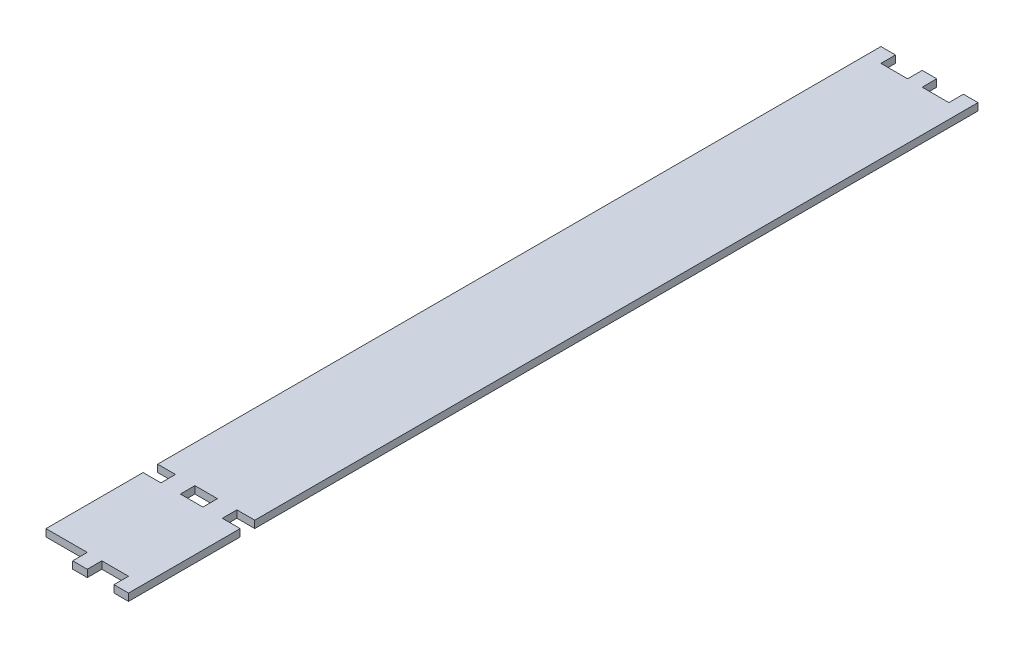
SolidWorks part; units mm, degrees
ref_plane "Plan de face" through (0, 0, 0) normal (0, 0, 1) x (1, 0, 0)
ref_plane "Plan de dessus" through (0, 0, 0) normal (0, 1, 0) x (1, 0, 0)
ref_plane "Plan de droite" through (0, 0, 0) normal (1, 0, 0) x (0, 0, -1)
sketch "Esquisse1" plane through (0, 0, 0) normal (0, 0, 1) x (1, 0, 0)
  line L1 (0, 0) -> (40, 0)
  line L2 (0, 0) -> (0, 3)
  line L3 (0, 3) -> (40, 3)
  line L4 (40, 0) -> (40, 3)
  dimension "D1" = 3
  dimension "D2" = 40
extrude "Boss.-Extru.1" add sketch "Esquisse1" along normal blind 338
sketch "Esquisse2" plane through (0, 3, 0) normal (0, 1, 0) x (1, 0, 0)
  line L0 (0, -292) -> (40, -292)
  line L1 (0, -298) -> (40, -298)
  line L2 (40, -298) -> (40, -292)
  line L3 (0, -292) -> (0, -298)
  line L8 (40, -338) -> (0, -338) construction
  line L9 (7.35, -292) -> (15.35, -292)
  line L10 (7.35, -292) -> (7.35, -298)
  line L11 (7.35, -298) -> (15.35, -298)
  line L12 (15.35, -292) -> (15.35, -298)
  line L13 (24.65, -292) -> (32.65, -292)
  line L14 (24.65, -292) -> (24.65, -298)
  line L15 (24.65, -298) -> (32.65, -298)
  line L16 (32.65, -292) -> (32.65, -298)
  line L17 (7.35, -292) -> (0, -292)
  line L18 (0, -338) -> (0, 0) construction
  line L19 (40, -338) -> (40, 0) construction
  line L20 (32.65, -292) -> (40, -292)
  line L21 (0, -292) -> (0, -298)
  line L23 (15.35, -298) -> (24.65, -298)
  line M2 (0, 0) -> (0, -338)
  line M4 (40, -338) -> (40, 0)
  dimension "D6" = 9.3
  dimension "D1" = 6
  dimension "D2" = 6
  dimension "D3" = 8
  dimension "D4" = 8
  dimension "D5" = 40
extrude "Enlèv. mat.-Extru.1" cut sketch "Esquisse2" against normal blind 6 contours L10 L0 L1 M2 | L14 L0 L12 L1 | L0 L16 L1 M4
sketch "Esquisse3" plane through (0, 0, 338) normal (0, 0, 1) x (1, 0, 0)
  line L0 (40, 3) -> (0, 3) construction
  line L1 (0, 3) -> (6, 3)
  line L2 (0, 3) -> (0, 0)
  line L3 (0, 0) -> (6, 0)
  line L4 (6, 3) -> (6, 0)
  line L5 (0, 0) -> (40, 0) construction
  line L6 (23, 3) -> (17, 3)
  line L7 (17, 3) -> (17, 0)
  line L8 (17, 0) -> (23, 0)
  line L9 (20, 3) -> (20, 0) construction
  line L10 (23, 3) -> (23, 0)
  line L11 (34, 3) -> (40, 3)
  line L12 (34, 3) -> (34, 0)
  line L13 (34, 0) -> (40, 0)
  line L14 (40, 3) -> (40, 0)
  point P18 (20, 3)
  dimension "D3" = 6
extrude "Boss.-Extru.2" add sketch "Esquisse3" along normal blind 6
ref_plane "Plan1" through (0, 0, 169) normal (0, 0, 1) x (1, 0, 0)
mirror "Symétrie1" about plane through (0, 0, 169) normal (0, 0, 1) of "Boss.-Extru.2"
sketch "Esquisse4" plane through (0, 0, 0) normal (0, -1, 0) x (1, 0, 0)
  line L0 (6, 338) -> (6, 344)
  line L1 (6, 338) -> (0, 338)
  line L2 (6, 344) -> (0, 344)
  line L3 (0, 338) -> (0, 344)
extrude "Enlèv. mat.-Extru.2" cut sketch "Esquisse4" against normal blind 6
